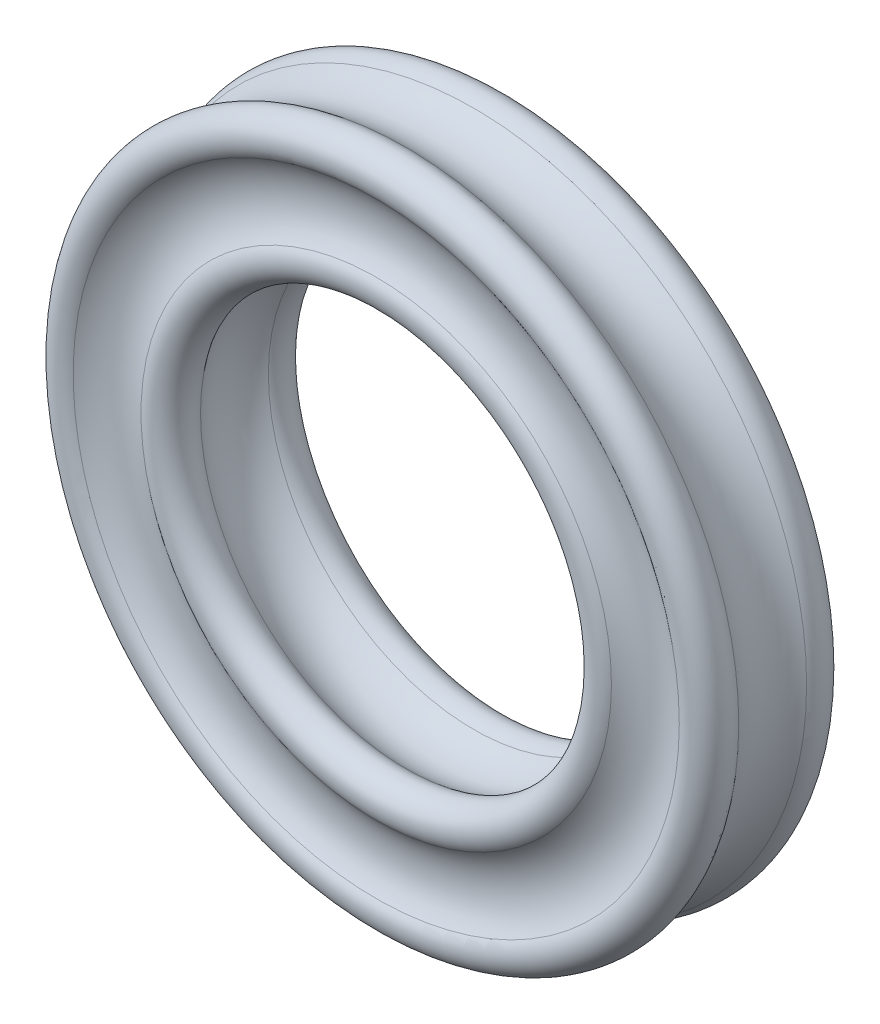
SolidWorks part; units mm, degrees
ref_plane "Front Plane" through (0, 0, 0) normal (0, 0, 1) x (1, 0, 0)
ref_plane "Top Plane" through (0, 0, 0) normal (0, 1, 0) x (1, 0, 0)
ref_plane "Right Plane" through (0, 0, 0) normal (1, 0, 0) x (0, 0, -1)
sketch "Sketch1" plane through (0, 0, 0) normal (1, 0, 0) x (0, 0, -1)
  line L0 (-1.3, 6.4) -> (1.3, 3.8) construction
  line L1 (1.3, 3.8) -> (1.3, 6.4) construction
  line L2 (1.3, 6.4) -> (-1.3, 6.4) construction
  line L3 (-1.3, 6.4) -> (-1.3, 3.8) construction
  line L4 (-1.3, 3.8) -> (1.3, 3.8) construction
  line L5 (1.3, 3.8) -> (1.2979, 3.7985)
  line L6 (-1.3, 3.8) -> (1.3, 6.4) construction
  line L7 (0, 0) -> (1.0659, 0) construction
  circle A0 centre (0, 5.1) radius 1.3 construction
  arc A1 (-0.6429, 6.3064) -> (-1.2064, 5.7429) centre (-0.9, 6) ccw
  arc A2 (0.6429, 6.3064) -> (1.2064, 5.7429) centre (0.9, 6) cw
  arc A3 (-1.2064, 4.4571) -> (-0.6429, 3.8936) centre (-0.9, 4.2) ccw
  arc A4 (0.6429, 3.8936) -> (1.2064, 4.4571) centre (0.9, 4.2) ccw
  arc A5 (-1.2064, 4.4571) -> (-1.2064, 5.7429) centre (-1.9724, 5.1) ccw
  arc A6 (-0.6429, 3.8936) -> (0.6429, 3.8936) centre (0, 3.1276) cw
  arc A7 (1.2064, 4.4571) -> (1.2064, 5.7429) centre (1.9724, 5.1) cw
  arc A8 (-0.6429, 6.3064) -> (0.6429, 6.3064) centre (0, 7.0724) ccw
  dimension "D3" = 0.4
  dimension "D4" = 1
  dimension "D1" = 2.6
  dimension "D2" = 3.8
revolve "Revolve1" add sketch "Sketch1" angle 360 about L7
